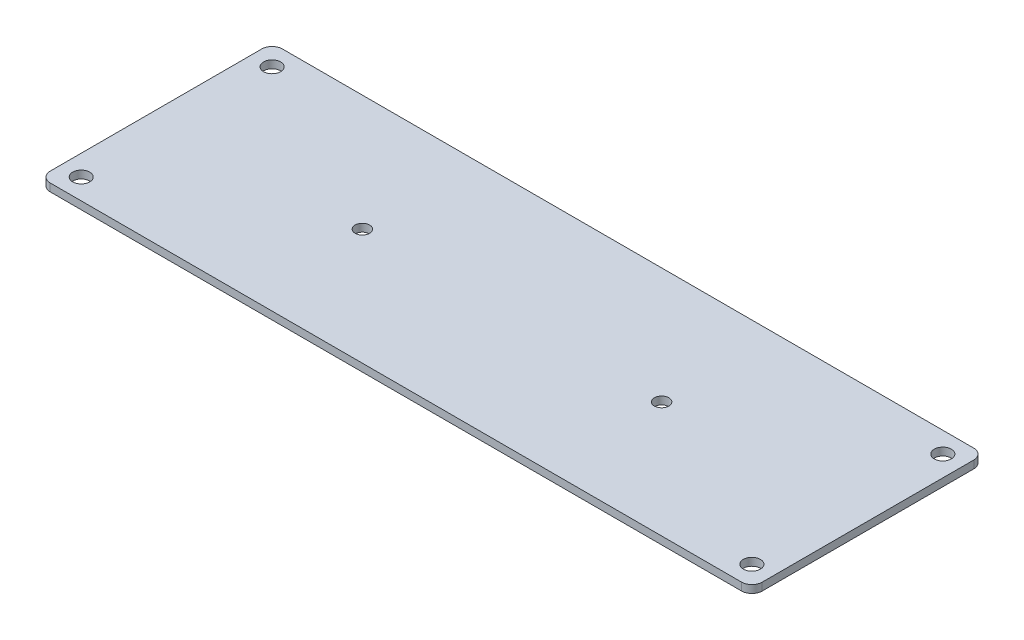
SolidWorks part; units mm, degrees
ref_plane "Front Plane" through (0, 0, 0) normal (0, 0, 1) x (1, 0, 0)
ref_plane "Top Plane" through (0, 0, 0) normal (0, 1, 0) x (1, 0, 0)
ref_plane "Right Plane" through (0, 0, 0) normal (1, 0, 0) x (0, 0, -1)
sketch "Sketch1" plane through (0, 0, 0) normal (0, 1, 0) x (1, 0, 0)
  line L0 (-29, 0) -> (0, 0) construction
  line L1 (69, -22.5) -> (-69, -22.5)
  line L2 (69, -22.5) -> (69, 22.5)
  line L3 (69, 22.5) -> (-69, 22.5)
  line L4 (-69, -22.5) -> (-69, 22.5)
  line L5 (69, -22.5) -> (-69, 22.5) construction
  line L6 (69, 22.5) -> (-69, -22.5) construction
  line L7 (0, 0) -> (29, 0) construction
  circle A0 centre (-29, 0) radius 1.4
  circle A1 centre (29, 0) radius 1.4
  point P0 (0, 0)
  dimension "D4" = 2.8
  dimension "D1" = 58
  dimension "D2" = 45
  dimension "D3" = 138
extrude "Boss-Extrude1" add sketch "Sketch1" along normal blind 1.5
sketch "Sketch2" plane through (0, 1.5, 0) normal (0, 1, 0) x (1, 0, 0)
  line L1 (65, -18.5) -> (-65, -18.5) construction
  line L2 (65, -18.5) -> (65, 18.5) construction
  line L3 (65, 18.5) -> (-65, 18.5) construction
  line L4 (-65, -18.5) -> (-65, 18.5) construction
  line L5 (65, -18.5) -> (-65, 18.5) construction
  line L6 (65, 18.5) -> (-65, -18.5) construction
  circle A0 centre (-65, 18.5) radius 1.65
  circle A1 centre (-65, -18.5) radius 1.65
  circle A2 centre (65, 18.5) radius 1.65
  circle A3 centre (65, -18.5) radius 1.65
  circle A4 centre (-65, 18.5) radius 3.5 construction
  point P0 (0, 0)
  dimension "D1" = 3.3
  dimension "D4" = 7
  dimension "D2" = 37
  dimension "D3" = 130
extrude "Cut-Extrude1" cut sketch "Sketch2" against normal through all
fillet "Fillet1" radius 2 4 edges at (-69, 0.75, -22.5) (69, 0.75, -22.5) (69, 0.75, 22.5) (-69, 0.75, 22.5)
